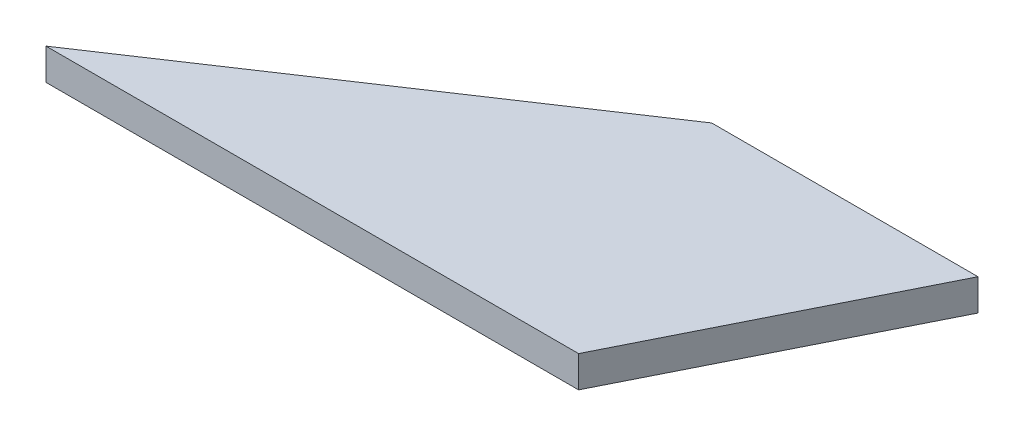
SolidWorks part; units mm, degrees
ref_plane "Front Plane" through (0, 0, 0) normal (0, 0, 1) x (1, 0, 0)
ref_plane "Top Plane" through (0, 0, 0) normal (0, 1, 0) x (1, 0, 0)
ref_plane "Right Plane" through (0, 0, 0) normal (1, 0, 0) x (0, 0, -1)
sketch "Sketch1" plane through (0, 0, 0) normal (0, 1, 0) x (1, 0, 0)
  line L0 (0, 0) -> (50.8, 0)
  line L1 (0, 0) -> (38.1, 25.4)
  line L2 (38.1, 25.4) -> (63.5, 25.4)
  line L3 (63.5, 25.4) -> (50.8, 0)
  point P3 (0, 0)
  point P6 (0, 0)
  point P7 (0, 0)
  point P8 (0, 0)
  point P9 (0, 0)
  point P10 (0, 0)
extrude "Boss-Extrude1" add sketch "Sketch1" along normal blind 3 contours L3 L0 L1 L2
